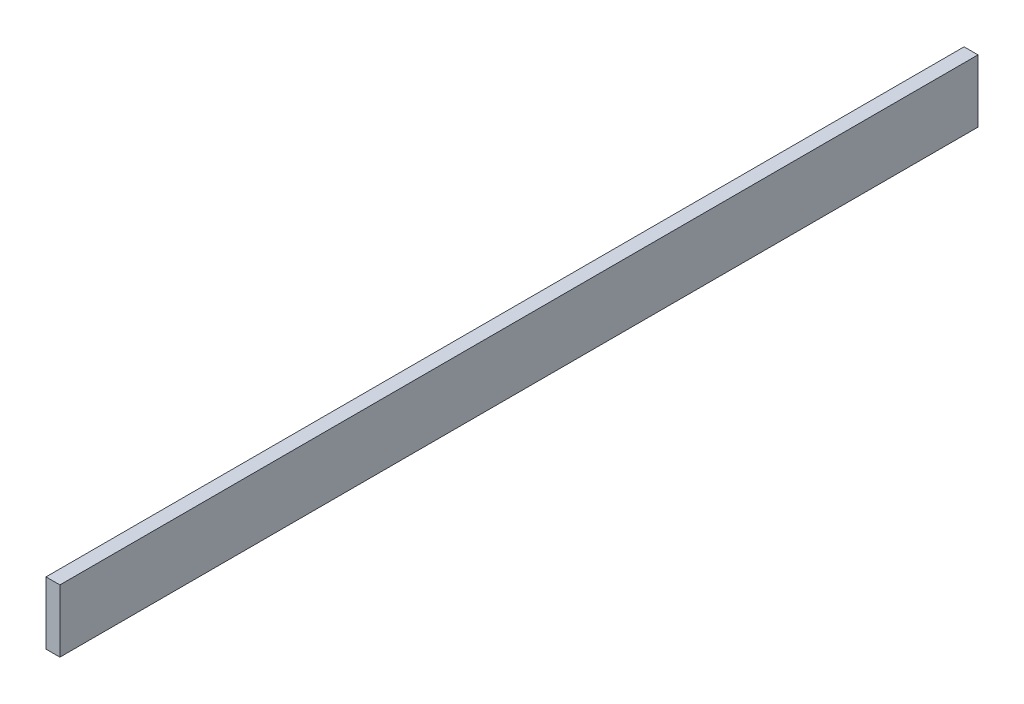
SolidWorks part; units mm, degrees
ref_plane "Plan de face" through (0, 0, 0) normal (0, 0, 1) x (1, 0, 0)
ref_plane "Plan de dessus" through (0, 0, 0) normal (0, 1, 0) x (1, 0, 0)
ref_plane "Plan de droite" through (0, 0, 0) normal (1, 0, 0) x (0, 0, -1)
sketch "Esquisse1" plane through (0, 0, 0) normal (1, 0, 0) x (0, 0, -1)
  line L1 (1192.1074, 28.7695) -> (-127.8926, 28.7695)
  line L2 (1192.1074, 28.7695) -> (1192.1074, -61.2305)
  line L3 (1192.1074, -61.2305) -> (-127.8926, -61.2305)
  line L4 (-127.8926, 28.7695) -> (-127.8926, -61.2305)
  dimension "D1" = 1320
  dimension "D2" = 90
extrude "Boss.-Extru.1" add sketch "Esquisse1" along normal blind 20
